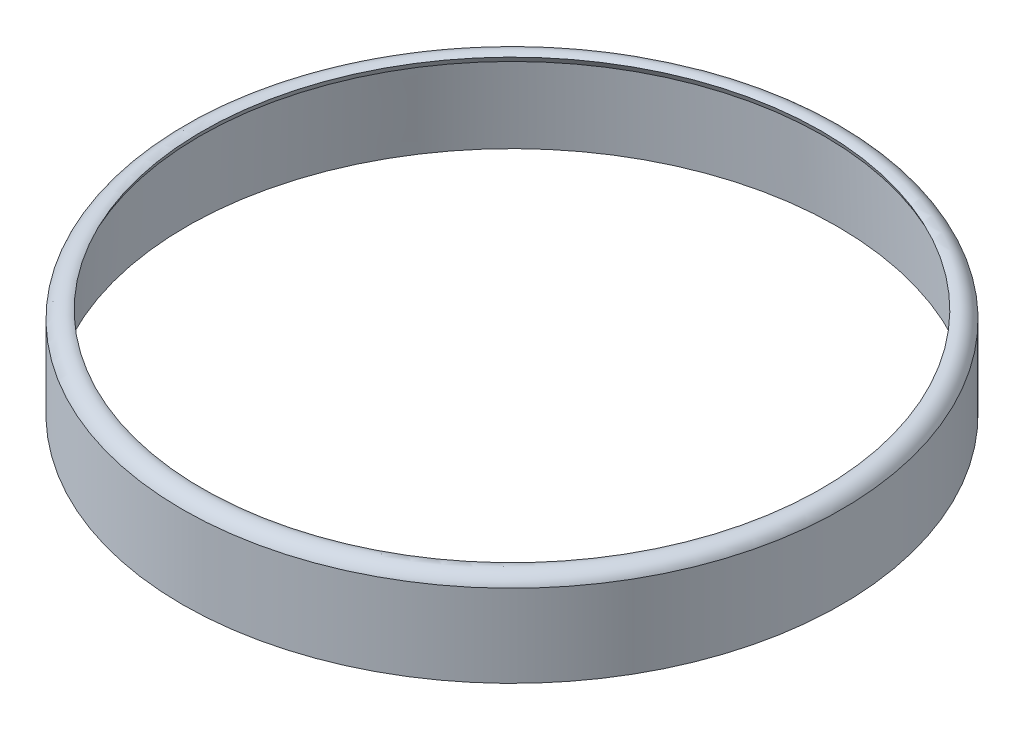
SolidWorks part; units mm, degrees
ref_plane "Front Plane" through (0, 0, 0) normal (0, 0, 1) x (1, 0, 0)
ref_plane "Top Plane" through (0, 0, 0) normal (0, 1, 0) x (1, 0, 0)
ref_plane "Right Plane" through (0, 0, 0) normal (1, 0, 0) x (0, 0, -1)
sketch "Sketch1" plane through (0, 0, 0) normal (0, 0, 1) x (1, 0, 0)
  line L0 (-160.0003, 0) -> (-160.0003, 40)
  line L1 (0, 0) -> (0, 100.0054) construction
  line L2 (-158.0003, 0) -> (-156.3059, 40)
  line L3 (-150.3109, 43.9098) -> (-151.5942, 41.179)
  line L4 (-160.0003, 0) -> (-158.0003, 0)
  arc A0 (-160.0003, 40) -> (-150.3109, 43.9098) centre (-153.3419, 37.46) cw
  arc A1 (-156.3059, 40) -> (-151.5942, 41.179) centre (-151.7381, 31.7494) cw
  dimension "D2" = 40
revolve "Revolve1" add sketch "Sketch1" angle 360 about L1
